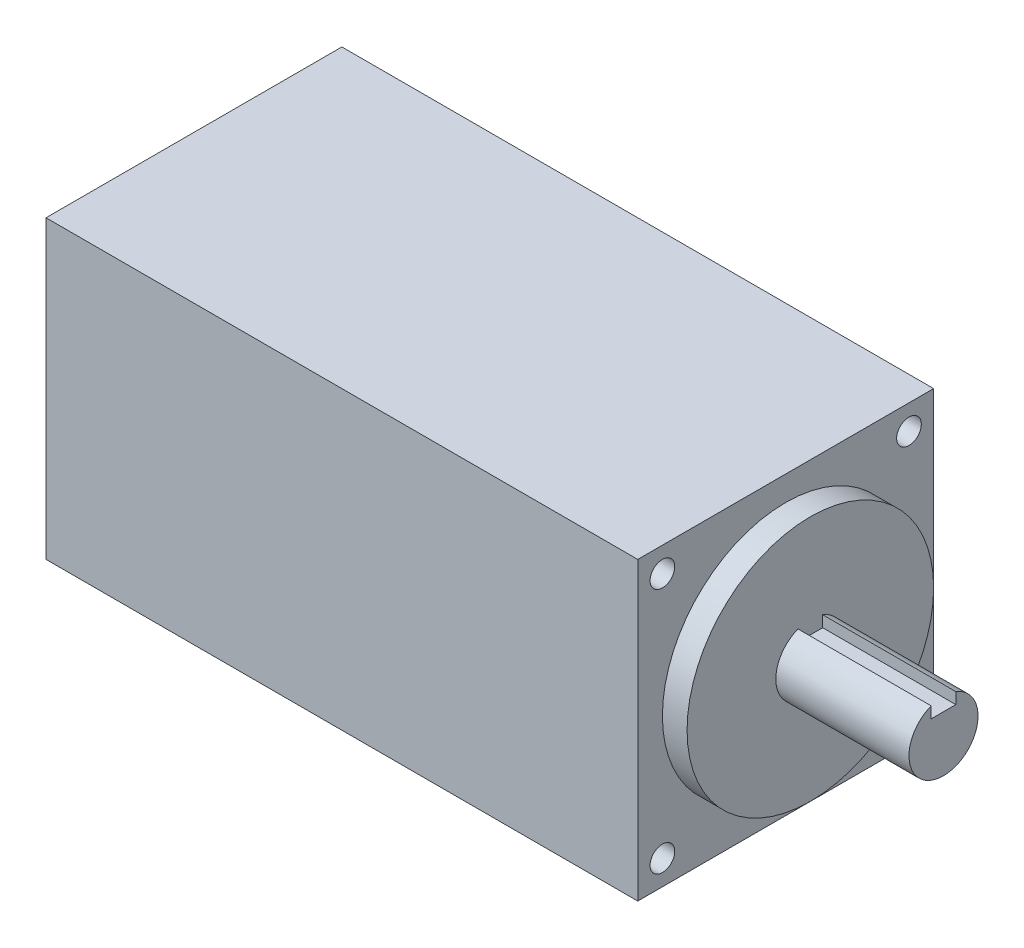
SolidWorks part; units mm, degrees
ref_plane "前视基准面" through (0, 0, 0) normal (0, 0, 1) x (1, 0, 0)
ref_plane "上视基准面" through (0, 0, 0) normal (0, 1, 0) x (1, 0, 0)
ref_plane "右视基准面" through (0, 0, 0) normal (1, 0, 0) x (0, 0, -1)
other "Configuration Table"
sketch "草图1" plane through (0, 0, 0) normal (1, 0, 0) x (0, 0, -1)
  line L1 (-30, -30) -> (30, -30)
  line L2 (-30, -30) -> (-30, 30)
  line L3 (-30, 30) -> (30, 30)
  line L4 (30, -30) -> (30, 30)
  line L5 (-30, -30) -> (30, 30) construction
  line L6 (-30, 30) -> (30, -30) construction
  point P0 (0, 0)
  dimension "D1" = 60
  dimension "D2" = 60
extrude "凸台-拉伸1" add sketch "草图1" against normal blind 120
sketch "草图2" plane through (0, 0, 0) normal (1, 0, 0) x (0, 0, -1)
  line L1 (-25, -25) -> (25, -25) construction
  line L2 (-25, -25) -> (-25, 25) construction
  line L3 (-25, 25) -> (25, 25) construction
  line L4 (25, -25) -> (25, 25) construction
  line L5 (-25, -25) -> (25, 25) construction
  line L6 (-25, 25) -> (25, -25) construction
  circle A0 centre (-25, 25) radius 2.5
  circle A1 centre (25, 25) radius 2.5
  circle A2 centre (-25, -25) radius 2.5
  circle A3 centre (25, -25) radius 2.5
  point P0 (0, 0)
  dimension "D3" = 5
  dimension "D4" = 5
  dimension "D5" = 5
  dimension "D6" = 5
  dimension "D1" = 50
  dimension "D2" = 50
extrude "切除-拉伸1" cut sketch "草图2" against normal blind 20
sketch "草图3" plane through (0, 0, 0) normal (1, 0, 0) x (0, 0, -1)
  circle A0 centre (0, 0) radius 25
  dimension "D1" = 50
extrude "凸台-拉伸2" add sketch "草图3" along normal blind 5
sketch "草图4" plane through (5, 0, 0) normal (1, 0, 0) x (0, 0, -1)
  circle A0 centre (0, 0) radius 7
  dimension "D1" = 14
extrude "凸台-拉伸3" add sketch "草图4" along normal blind 27
sketch "草图5" plane through (32, 0, 0) normal (1, 0, 0) x (0, 0, -1)
  line L0 (-2.5, 4.2512) -> (2.5, 4.2512)
  line L1 (-2.5, -7) -> (2.5, -7) construction
  line L2 (-2.5, 4.2512) -> (-2.5, 7)
  line L3 (-2.5, 7) -> (2.5, 7)
  line L4 (2.5, 4.2512) -> (2.5, 7)
  line L5 (-2.5, -7) -> (2.5, 7) construction
  line L6 (-2.5, 7) -> (2.5, -7) construction
  point P0 (0, 0)
  point P8 (0, 0)
  dimension "D1" = 5
  dimension "D2" = 14
  dimension "D3" = 11.2512
extrude "切除-拉伸2" cut sketch "草图5" against normal blind 27
